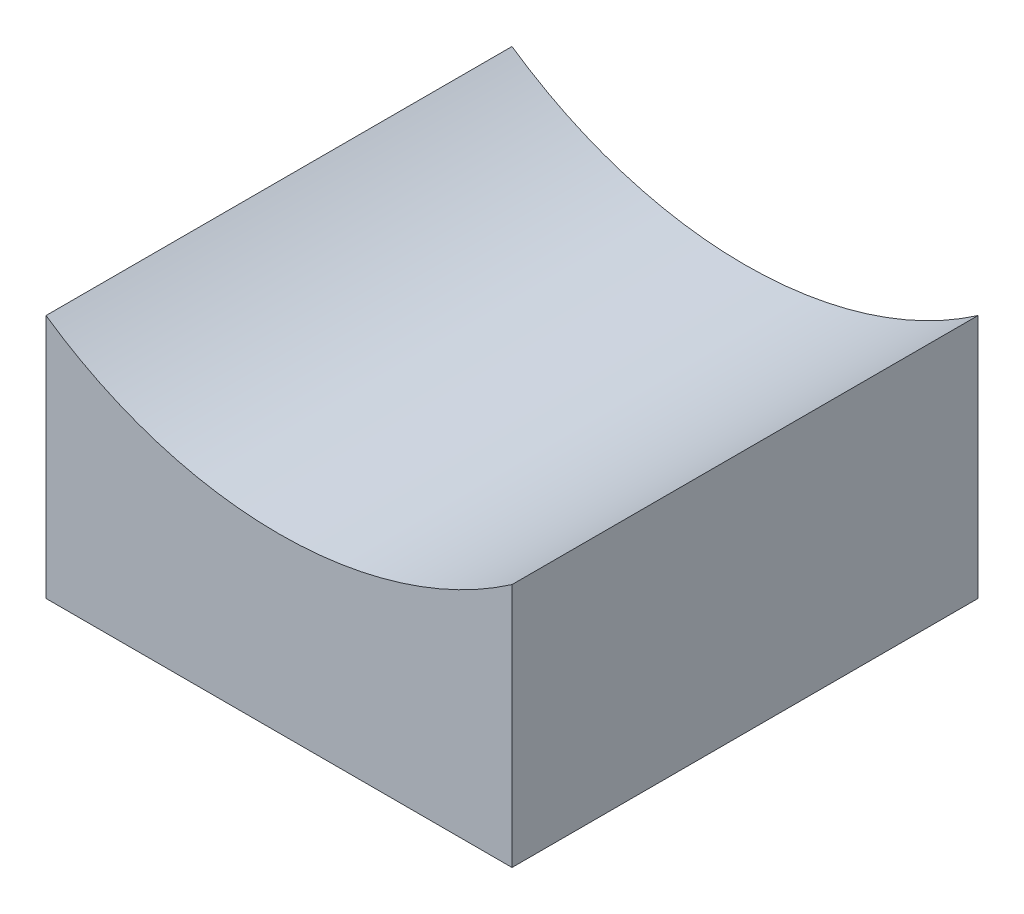
SolidWorks part; units mm, degrees
material "ABS"
ref_plane "Front Plane" through (0, 0, 0) normal (0, 0, 1) x (1, 0, 0)
ref_plane "Top Plane" through (0, 0, 0) normal (0, 1, 0) x (1, 0, 0)
ref_plane "Right Plane" through (0, 0, 0) normal (1, 0, 0) x (0, 0, -1)
sketch "Sketch1" plane through (0, 0, 0) normal (0, 0, 1) x (1, 0, 0)
  line L0 (12.7, 0) -> (-12.7, 0)
  line L1 (-12.7, 0) -> (-12.7, 13.3565)
  line L2 (12.7, 0) -> (12.7, 13.3565)
  arc A1 (-12.7, 13.3565) -> (12.7, 13.3565) centre (0, 31.75) ccw
  point P4 (0, 0)
  point P8 (-12.7, 15.512)
  point P9 (0, 0)
  dimension "D1" = 22.352
  dimension "D2" = 31.75
  dimension "D3" = 25.4
extrude "Boss-Extrude1" add sketch "Sketch1" along normal blind 25.4
